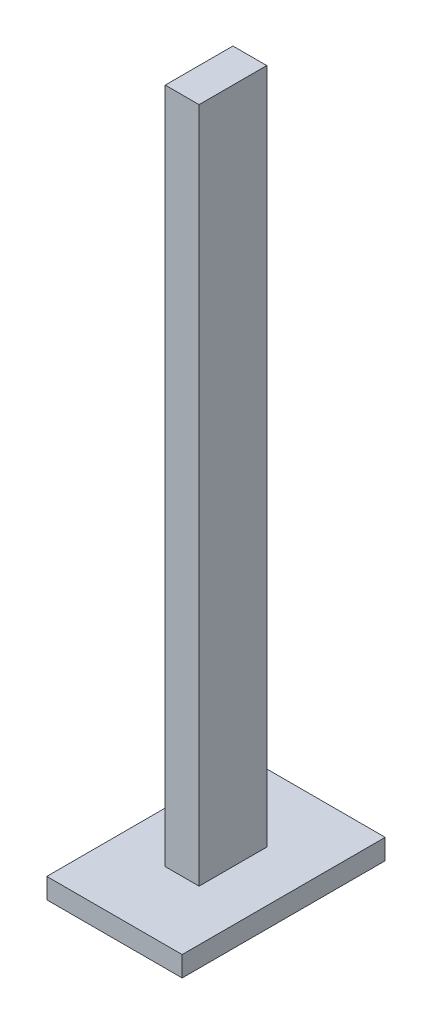
SolidWorks part; units mm, degrees
ref_plane "Front Plane" through (0, 0, 0) normal (0, 0, 1) x (1, 0, 0)
ref_plane "Top Plane" through (0, 0, 0) normal (0, 1, 0) x (1, 0, 0)
ref_plane "Right Plane" through (0, 0, 0) normal (1, 0, 0) x (0, 0, -1)
sketch "Sketch1" plane through (0, 0, 0) normal (0, 1, 0) x (1, 0, 0)
  line L1 (-25.4, -38.1) -> (25.4, -38.1)
  line L2 (-25.4, -38.1) -> (-25.4, 38.1)
  line L3 (-25.4, 38.1) -> (25.4, 38.1)
  line L4 (25.4, -38.1) -> (25.4, 38.1)
  line L5 (-25.4, -38.1) -> (25.4, 38.1) construction
  line L6 (-25.4, 38.1) -> (25.4, -38.1) construction
  point P0 (0, 0)
  dimension "D1" = 76.2
  dimension "D2" = 50.8
extrude "Boss-Extrude1" add sketch "Sketch1" along normal blind 7.62
sketch "Sketch2" plane through (0, 7.62, 0) normal (0, 1, 0) x (1, 0, 0)
  line L1 (-6.35, -12.7) -> (6.35, -12.7)
  line L2 (-6.35, -12.7) -> (-6.35, 12.7)
  line L3 (-6.35, 12.7) -> (6.35, 12.7)
  line L4 (6.35, -12.7) -> (6.35, 12.7)
  line L5 (-6.35, -12.7) -> (6.35, 12.7) construction
  line L6 (-6.35, 12.7) -> (6.35, -12.7) construction
  point P0 (0, 0)
  dimension "D1" = 25.4
  dimension "D2" = 12.7
extrude "Boss-Extrude2" add sketch "Sketch2" along normal blind 254
